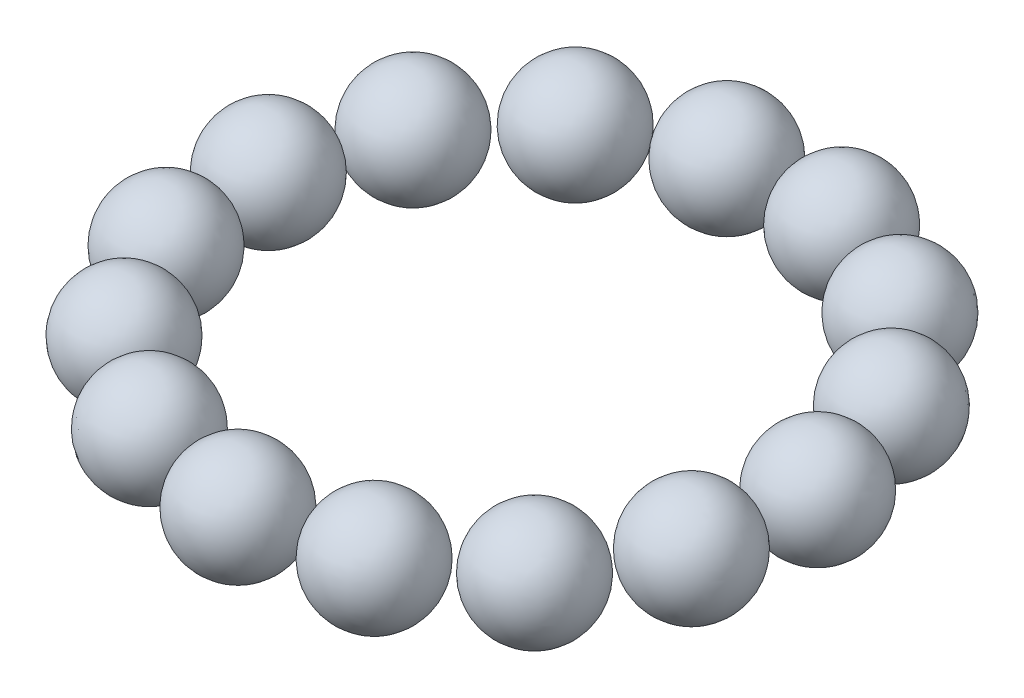
SolidWorks part; units mm, degrees
material "Chrome Stainless Steel"
ref_plane "Front Plane" through (0, 0, 0) normal (1, 0, 0) x (0, 1, 0)
ref_plane "Top Plane" through (0, 0, 0) normal (0, 0, 1) x (0, 1, 0)
ref_plane "Right Plane" through (0, 0, 0) normal (0, 1, 0) x (-1, 0, 0)
sketch "Sketch2" plane through (0, 0, 0) normal (1, 0, 0) x (0, 1, 0)
  line L0 (-31.8153, 0) -> (28.7982, 0) construction
  line L1 (0, 24) -> (0, -22.0859) construction
  line L2 (-4, 20) -> (4, 20)
  arc A0 (-4, 20) -> (4, 20) centre (0, 20) cw
  circle A1 centre (0, 0) radius 10
  point P8 (0, 20)
  point P10 (0, 24)
  dimension "D2" = 4
  dimension "D4" = 20
  dimension "D1" = 20
  dimension "D3" = 8
revolve "Revolve1" add sketch "Sketch2" angle 360 about L2
pattern_circular "CirPattern2" count 15 over 360 about axis through (0, 0, 0) along (0, 1, 0) of bodies 101
